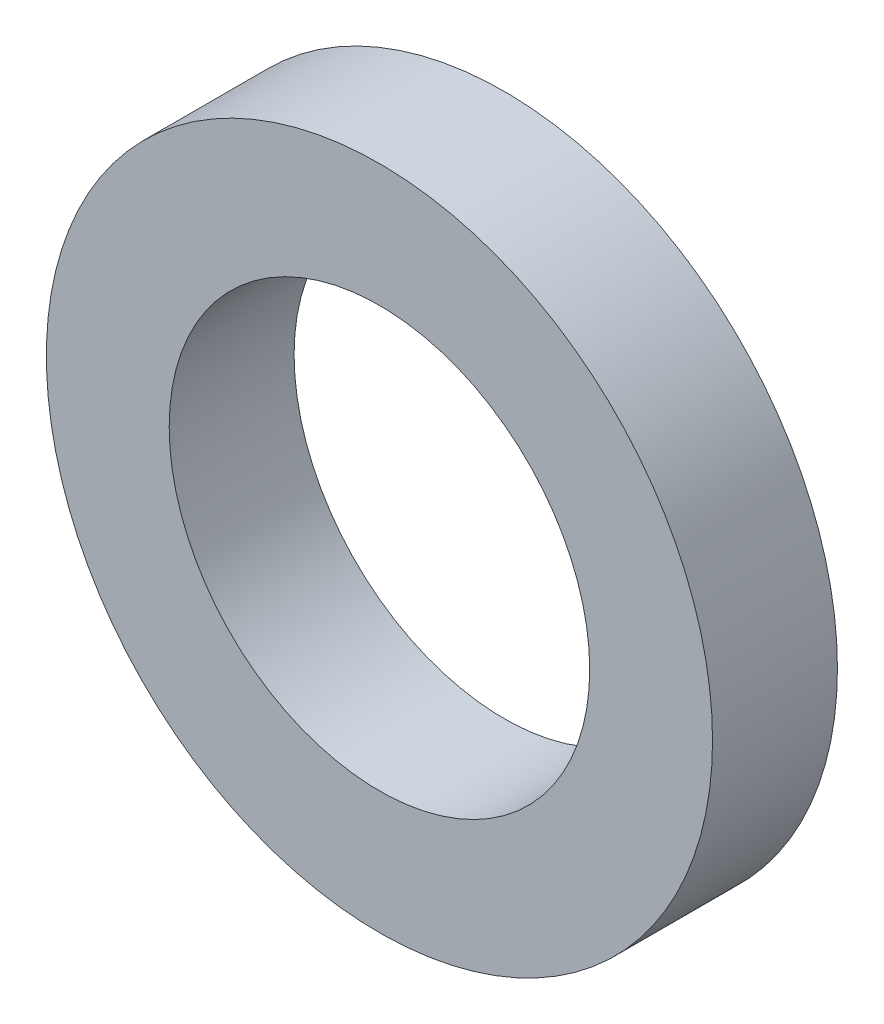
SolidWorks part; units mm, degrees
ref_plane "Front Plane" through (0, 0, 0) normal (0, 0, 1) x (1, 0, 0)
ref_plane "Top Plane" through (0, 0, 0) normal (0, 1, 0) x (1, 0, 0)
ref_plane "Right Plane" through (0, 0, 0) normal (1, 0, 0) x (0, 0, -1)
sketch "Sketch1" plane through (0, 0, 0) normal (0, 0, 1) x (1, 0, 0)
  circle A0 centre (0, 0) radius 16
  circle A1 centre (0, 0) radius 10.1
  dimension "D1" = 32
  dimension "D2" = 20.2
extrude "Boss-Extrude1" add sketch "Sketch1" along normal mid plane 6
